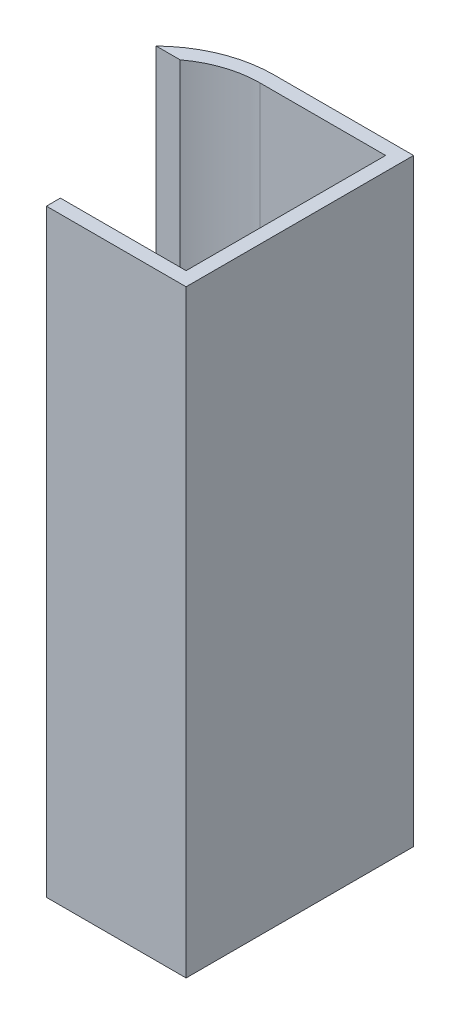
SolidWorks part; units mm, degrees
ref_plane "Front Plane" through (0, 0, 0) normal (0, 0, 1) x (1, 0, 0)
ref_plane "Top Plane" through (0, 0, 0) normal (0, 1, 0) x (1, 0, 0)
ref_plane "Right Plane" through (0, 0, 0) normal (1, 0, 0) x (0, 0, -1)
sketch "Sketch1" plane through (0, 0, 0) normal (0, 1, 0) x (1, 0, 0)
  line L0 (7, 57) -> (7, -57)
  line L1 (7, -57) -> (-63, -57)
  line L2 (7, 57) -> (-63, 57)
  line L3 (-105, 40) -> (-93, 40)
  line L4 (-63, -57) -> (-63, -50)
  line L5 (-63, 50) -> (0, 50)
  line L6 (0, 50) -> (0, -50)
  line L7 (0, -50) -> (-63, -50)
  line L8 (0, 0) -> (-95.2381, 0) construction
  arc A1 (-63, 57) -> (-105, 40) centre (-63, -3.3824) ccw
  arc A2 (-93, 40) -> (-63, 50) centre (-63, 0) cw
  point P14 (-31.5, -50)
  point P16 (0, 0)
  point P17 (-58.1274, -1.8541)
  point P18 (-110.6272, 38.9928)
  point P19 (-106.8039, 40)
  dimension "D8" = 30
  dimension "D9" = 10
  dimension "D1" = 50
  dimension "D2" = 50
  dimension "D3" = 7
  dimension "D4" = 7
  dimension "D5" = 7
  dimension "D6" = 0
  dimension "D7" = 70
  dimension "D10" = 12
extrude "Boss-Extrude2" add sketch "Sketch1" along normal blind 300
